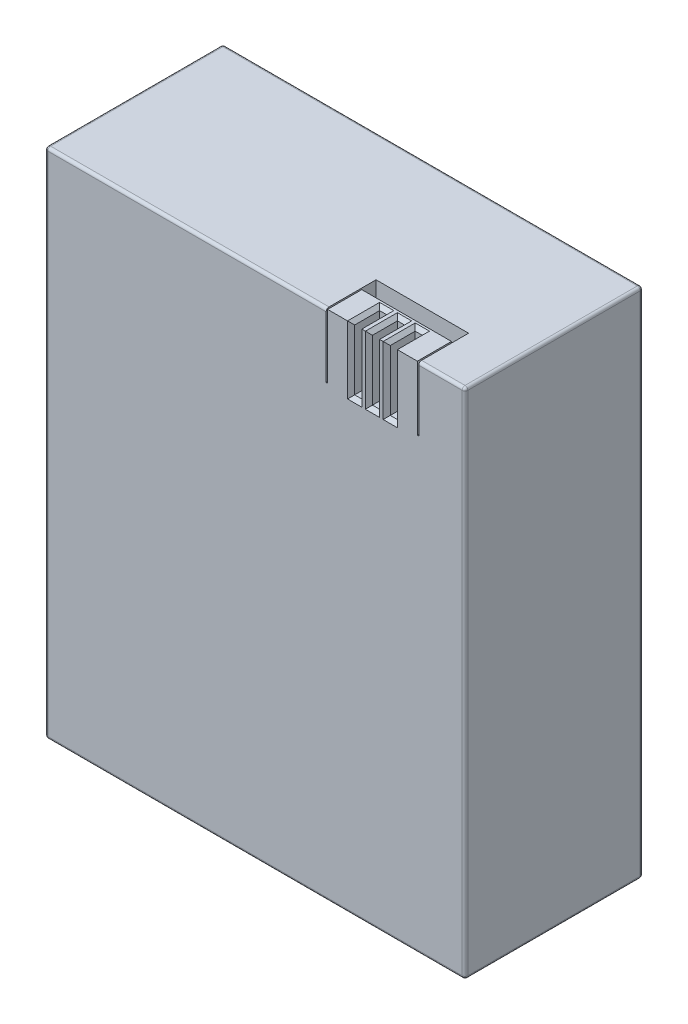
SolidWorks part; units mm, degrees
ref_plane "Front Plane" through (0, 0, 0) normal (0, 0, 1) x (1, 0, 0)
ref_plane "Top Plane" through (0, 0, 0) normal (0, 1, 0) x (1, 0, 0)
ref_plane "Right Plane" through (0, 0, 0) normal (1, 0, 0) x (0, 0, -1)
sketch "Sketch1" plane through (0, 0, 0) normal (0, 0, 1) x (1, 0, 0)
  line L0 (0, 0) -> (0, 8.7125) construction
  line L1 (0, 0) -> (10.9681, 0) construction
  line L3 (-14.75, 18) -> (14.75, 18)
  line L4 (-14.75, 18) -> (-14.75, -18)
  line L5 (-14.75, -18) -> (14.75, -18)
  line L6 (14.75, 18) -> (14.75, -18)
  dimension "D1" = 36
  dimension "D2" = 29.5
extrude "Boss-Extrude1" add sketch "Sketch1" along normal blind 12.5
sketch "Sketch3" plane through (0, 0, 12.5) normal (0, 0, 1) x (1, 0, 0)
  line L0 (14.75, 14.5) -> (8.25, 14.5) construction
  line L1 (14.75, -18) -> (14.75, 18) construction
  line L2 (8.25, 14.5) -> (8.25, 18) construction
  line L3 (14.75, 18) -> (-14.75, 18) construction
  line L4 (8.5, 15.5) -> (8.5, 18.6226)
  line L5 (8.25, 14.5) -> (9.5, 14.5) construction
  line L6 (8, 15.5) -> (8, 13.5)
  line L7 (8, 13.5) -> (8.5, 13.5)
  line L8 (8.5, 15.5) -> (8.5, 13.5)
  line L9 (8.5, 18.6226) -> (8, 18.6226)
  line L10 (8, 18.6226) -> (8, 15.5)
  line L11 (9.5, 14.5) -> (9.5, 15.8106) construction
  line L12 (9.25, 18.6226) -> (9.75, 18.6226)
  line L13 (9.25, 18.6226) -> (9.25, 13.5)
  line L14 (9.25, 13.5) -> (9.75, 13.5)
  line L15 (9.75, 18.6226) -> (9.75, 13.5)
  line L16 (8.5, 13.5) -> (10.7345, 13.5) construction
  line L17 (8.25, 14.5) -> (7, 14.5) construction
  line L18 (7, 14.5) -> (7, 15.6834) construction
  line L20 (6.75, 18.9275) -> (7.25, 18.9275)
  line L21 (6.75, 18.9275) -> (6.75, 13.5)
  line L22 (6.75, 13.5) -> (7.25, 13.5)
  line L23 (7.25, 18.9275) -> (7.25, 13.5)
  dimension "D1" = 6.5
  dimension "D2" = 3.5
  dimension "D3" = 1.25
  dimension "D4" = 0.5
  dimension "D5" = 0.5
  dimension "D6" = 1.25
  dimension "D7" = 0.5
  dimension "D8" = 1
  dimension "D9" = 1
extrude "Cut-Extrude1" cut sketch "Sketch3" against normal blind 2
chamfer "Chamfer1" distance 0.25 angle 45 18 edges at (9.25, 18, 11.5) (9.5, 18, 10.5) (9.75, 18, 11.5) (9.75, 15.75, 12.5) (9.5, 13.5, 12.5) (9.25, 15.75, 12.5) (8.25, 13.5, 12.5) (8.5, 15.75, 12.5) (8.5, 18, 11.5) (8, 15.75, 12.5) (8.25, 18, 10.5) (8, 18, 11.5) (7, 18, 10.5) (7.25, 18, 11.5) (7.25, 15.75, 12.5) (7, 13.5, 12.5) (6.75, 15.75, 12.5) (6.75, 18, 11.5)
sketch "Sketch4" plane through (0, 18, 0) normal (0, 1, 0) x (1, 0, 0)
  line L0 (14.75, -12.5) -> (10, -12.5) construction
  line L1 (5, -9) -> (11.5, -9)
  line L2 (5, -9) -> (5, -13.5)
  line L3 (5.1, -10.1) -> (5.1, -13.5)
  line L4 (11.5, -9) -> (11.5, -12.5)
  line L5 (8.25, -10.5) -> (8.25, -10.4718) construction
  line L6 (8.5, -10.5) -> (8, -10.5) construction
  line L7 (5.1, -10.1) -> (11.4, -10.1)
  line L8 (11.4, -10.1) -> (11.4, -13.5)
  line L9 (5.1, -13.5) -> (5.1, -13.5487)
  line L10 (5.1, -13.5487) -> (5, -13.5487)
  line L11 (5, -13.5487) -> (5, -13.5)
  line L12 (11.4, -13.5) -> (11.4, -13.5903)
  line L13 (11.4, -13.5903) -> (11.5, -13.5903)
  line L14 (11.5, -13.5903) -> (11.5, -12.5)
  dimension "D1" = 6.5
  dimension "D2" = 3.5
  dimension "D3" = 0.1
extrude "Cut-Extrude2" cut sketch "Sketch4" against normal up to surface (4.5 mm away) up to face at (8.25, 13.5, 11.375)
fillet "Fillet1" radius 0.2 13 edges at (-14.75, -18, 6.25) (0, -18, 12.5) (14.75, -18, 6.25) (0, -18, 0) (-14.75, 0, 0) (14.75, 0, 0) (14.75, 0, 12.5) (-14.75, 0, 12.5) (0, 18, 0) (-14.75, 18, 6.25) (-4.875, 18, 12.5) (13.125, 18, 12.5) (14.75, 18, 6.25)
